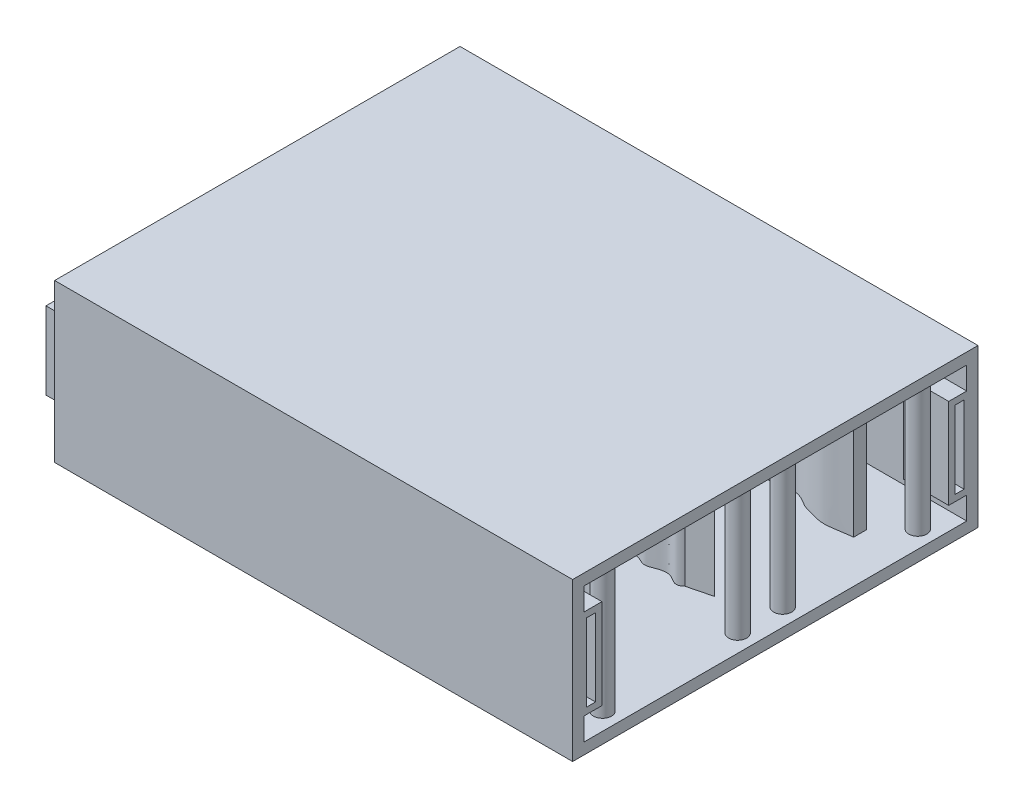
SolidWorks part; units mm, degrees
ref_plane "Спереди" through (0, 0, 0) normal (0, 0, 1) x (1, 0, 0)
ref_plane "Сверху" through (0, 0, 0) normal (0, 1, 0) x (1, 0, 0)
ref_plane "Справа" through (0, 0, 0) normal (1, 0, 0) x (0, 0, -1)
sketch "Эскиз1" plane through (0, 0, 0) normal (0, 1, 0) x (1, 0, 0)
  line L1 (-57.5, -45) -> (57.5, -45)
  line L2 (-57.5, -45) -> (-57.5, 45)
  line L3 (-57.5, 45) -> (57.5, 45)
  line L4 (57.5, -45) -> (57.5, 45)
  line L5 (-57.5, -45) -> (57.5, 45) construction
  line L6 (-57.5, 45) -> (57.5, -45) construction
  point P0 (0, 0)
extrude "Бобышка-Вытянуть1" add sketch "Эскиз1" along normal blind 35
sketch "Эскиз2" plane through (57.5, 0, 0) normal (1, 0, 0) x (0, 0, -1)
  line L0 (0, -1000) -> (0, 49000) construction
  line L1 (-1045, 17.5) -> (48955, 17.5) construction
  line L2 (-45, 35) -> (-45, 0) construction
  line L4 (-42.5, 2.5) -> (42.5, 2.5)
  line L5 (-42.5, 2.5) -> (-42.5, 32.5)
  line L6 (-42.5, 32.5) -> (42.5, 32.5)
  line L7 (42.5, 2.5) -> (42.5, 32.5)
  line L8 (-42.5, 2.5) -> (42.5, 32.5) construction
  line L9 (-42.5, 32.5) -> (42.5, 2.5) construction
  point P4 (0, 17.5)
  point P8 (-45, 17.5)
extrude "Вырез-Вытянуть1" cut sketch "Эскиз2" against normal through all
sketch "Эскиз3" plane through (57.5, 0, 0) normal (1, 0, 0) x (0, 0, -1)
  line L0 (38.5, 27.5) -> (42.5, 27.5)
  line L1 (-42.5, 32.5) -> (-42.5, 2.5) construction
  line L2 (42.5, 27.5) -> (42.5, 7.5)
  line L3 (-42.5, 7.5) -> (-42.5, 27.5)
  line L4 (-42.5, 27.5) -> (-38.5, 27.5)
  line L5 (-38.5, 27.5) -> (-38.5, 7.5)
  line L6 (-38.5, 7.5) -> (-42.5, 7.5)
  line L7 (42.5, 7.5) -> (38.5, 7.5)
  line L8 (38.5, 7.5) -> (38.5, 27.5)
  dimension "D1" = 2
extrude "Бобышка-Вытянуть2" add sketch "Эскиз3" against normal blind 10
pattern_linear "Линейный массив1" count 2 spacing 105 along (-1, 0, 0) of "Бобышка-Вытянуть2"
sketch "Эскиз4" plane through (-57.5, 0, 0) normal (-1, 0, 0) x (0, 0, 1)
  line L2 (-39.9142, 8.9142) -> (-39.9142, 26.0858)
  line L3 (-39.9142, 26.0858) -> (-41.9142, 26.0858)
  line L4 (-41.9142, 26.0858) -> (-41.9142, 8.9142)
  line L5 (-41.9142, 8.9142) -> (-39.9142, 8.9142)
  line L6 (39.9142, 8.9142) -> (39.9142, 26.0858)
  line L7 (39.9142, 26.0858) -> (41.9184, 26.0858)
  line L8 (41.9184, 26.0858) -> (41.9184, 8.9142)
  line L9 (41.9184, 8.9142) -> (39.9142, 8.9142)
extrude "Бобышка-Вытянуть3" add sketch "Эскиз4" along normal blind 5
sketch "Эскиз5" plane through (57.5, 0, 0) normal (1, 0, 0) x (0, 0, -1)
  line L1 (39.9142, 26.0858) -> (41.9142, 26.0858)
  line L2 (-39.9142, 8.9142) -> (-39.9142, 26.0858)
  line L3 (-41.8615, 26.0858) -> (-41.9142, 26.0858)
  line L4 (-41.9142, 26.0858) -> (-39.9142, 26.0858)
  line L5 (-41.9142, 26.0858) -> (-41.9142, 8.9142)
  line L6 (-41.9142, 8.9142) -> (-39.9142, 8.9142)
  line L7 (41.9142, 26.0858) -> (41.9142, 8.9142)
  line L8 (41.9142, 8.9142) -> (39.9142, 8.9142)
  line L9 (39.9142, 8.9142) -> (39.9142, 26.0858)
extrude "Вырез-Вытянуть2" cut sketch "Эскиз5" against normal blind 5 contours L5 L6 L2 L4 L3 | L9 L8 L7 L1
sketch "Эскиз6" plane through (0, 2.5, 0) normal (0, 1, 0) x (1, 0, 0)
  line L2 (-46.0433, 8.2412) -> (-46.0433, 6.421)
  line L3 (-46.0433, -8.2412) -> (-46.0433, -6.421)
  line L4 (-8.1582, 11.8084) -> (-8.1582, 10.8243)
  line L5 (-8.1582, -11.8084) -> (-8.1582, -10.8243)
  line L6 (3.0352, 28.6599) -> (3.0352, 26.8012)
  line L7 (3.0352, -28.6599) -> (3.0352, -26.8012)
  line L8 (48.0545, 29.6439) -> (48.0545, 26.8012)
  line L9 (48.0545, -29.6439) -> (48.0545, -26.8012)
  line L12 (38.7427, 1.3315) -> (43.9954, 0)
  line L13 (38.7427, -1.3315) -> (43.9954, 0)
  line L14 (5.3057, 0.9403) -> (1.7103, 0)
  line L15 (5.3057, -0.9403) -> (1.7103, 0)
  spline S0 degree 3 poles (-46.0433, 8.2412) (-43.7421, 7.0712) (-39.4784, 8.2572) (-34.0078, 11.3843) (-27.9935, 11.7331) (-23.0026, 8.3658) (-15.5011, 8.856) (-11.9371, 13.5591) (-8.1582, 11.8084) knots 0 0 0 0 0.182781 0.315256 0.483432 0.602003 0.761083 1 1 1 1
  spline S1 degree 3 poles (-46.0433, -8.2412) (-43.7421, -7.0712) (-39.4784, -8.2572) (-34.0078, -11.3843) (-27.9935, -11.7331) (-23.0026, -8.3658) (-15.5011, -8.856) (-11.9371, -13.5591) (-8.1582, -11.8084) knots 0 0 0 0 0.182781 0.315256 0.483432 0.602003 0.761083 1 1 1 1
  spline S2 degree 3 poles (3.0352, 28.6599) (5.7308, 30.3357) (11.3056, 31.2251) (17.9095, 26.7103) (24.746, 28.1237) (31.2421, 31.5672) (38.8642, 27.6886) (45.0279, 26.8022) (48.0545, 29.6439) knots 0 0 0 0 0.205733 0.319851 0.488896 0.620938 0.765565 1 1 1 1
  spline S3 degree 3 poles (3.0352, -28.6599) (5.7308, -30.3357) (11.3056, -31.2251) (17.9095, -26.7103) (24.746, -28.1237) (31.2421, -31.5672) (38.8642, -27.6886) (45.0279, -26.8022) (48.0545, -29.6439) knots 0 0 0 0 0.205733 0.319851 0.488896 0.620938 0.765565 1 1 1 1
  spline S4 degree 3 poles (-46.0433, 6.421) (-45.5676, 6.783) (-44.4183, 6.6635) (-42.5968, 6.252) (-40.6755, 6.8619) (-38.947, 7.5486) (-37.3717, 8.2728) (-35.9222, 9.1358) (-34.368, 9.7951) (-32.5524, 10.2365) (-30.8751, 10.4841) (-29.2057, 10.0746) (-27.7221, 9.7288) (-26.0326, 9.1727) (-24.419, 8.156) (-22.5797, 7.4979) (-20.5124, 7.6511) (-18.4237, 7.7038) (-16.431, 8.8517) (-14.5367, 9.6878) (-12.9332, 10.9205) (-10.7592, 11.5161) (-9.0869, 11.3699) (-8.1582, 10.8243) knots 0 0 0 0 0.041686 0.082662 0.139028 0.187024 0.22312 0.268386 0.313304 0.348627 0.408584 0.437027 0.476454 0.522986 0.568955 0.61917 0.665389 0.723193 0.772338 0.834418 0.878554 0.921772 1 1 1 1
  spline S5 degree 3 poles (-46.0433, -6.421) (-45.5676, -6.783) (-44.4183, -6.6635) (-42.5968, -6.252) (-40.6755, -6.8619) (-38.947, -7.5486) (-37.3717, -8.2728) (-35.9222, -9.1358) (-34.368, -9.7951) (-32.5524, -10.2365) (-30.8751, -10.4841) (-29.2057, -10.0746) (-27.7221, -9.7288) (-26.0326, -9.1727) (-24.419, -8.156) (-22.5797, -7.4979) (-20.5124, -7.6511) (-18.4237, -7.7038) (-16.431, -8.8517) (-14.5367, -9.6878) (-12.9332, -10.9205) (-10.7592, -11.5161) (-9.0869, -11.3699) (-8.1582, -10.8243) knots 0 0 0 0 0.041686 0.082662 0.139028 0.187024 0.22312 0.268386 0.313304 0.348627 0.408584 0.437027 0.476454 0.522986 0.568955 0.61917 0.665389 0.723193 0.772338 0.834418 0.878554 0.921772 1 1 1 1
  spline S6 degree 3 poles (3.0352, 26.8012) (4.5327, 27.5866) (6.4341, 29.0654) (9.093, 28.9982) (10.2266, 28.4562) (11.4665, 28.2431) (12.7306, 27.7946) (14.2593, 27.2906) (16.0122, 26.465) (18.2233, 26.1483) (20.6462, 25.8486) (22.9995, 26.3015) (25.2825, 27.0627) (27.1697, 28.3) (29.2098, 28.8951) (31.1988, 29.0558) (33.2315, 29.152) (35.1044, 28.3801) (36.7544, 27.2044) (38.7976, 26.8575) (41.0011, 26.0539) (44.2057, 26.1287) (46.5076, 26.719) (48.0545, 26.8012) knots 0 0 0 0 0.110987 0.140256 0.164303 0.1902 0.220041 0.2497 0.292932 0.342679 0.391189 0.447844 0.493596 0.543981 0.590585 0.627098 0.671558 0.718423 0.753047 0.799494 0.848039 0.901888 1 1 1 1
  spline S7 degree 3 poles (3.0352, -26.8012) (4.5327, -27.5866) (6.4341, -29.0654) (9.093, -28.9982) (10.2266, -28.4562) (11.4665, -28.2431) (12.7306, -27.7946) (14.2593, -27.2906) (16.0122, -26.465) (18.2233, -26.1483) (20.6462, -25.8486) (22.9995, -26.3015) (25.2825, -27.0627) (27.1697, -28.3) (29.2098, -28.8951) (31.1988, -29.0558) (33.2315, -29.152) (35.1044, -28.3801) (36.7544, -27.2044) (38.7976, -26.8575) (41.0011, -26.0539) (44.2057, -26.1287) (46.5076, -26.719) (48.0545, -26.8012) knots 0 0 0 0 0.110987 0.140256 0.164303 0.1902 0.220041 0.2497 0.292932 0.342679 0.391189 0.447844 0.493596 0.543981 0.590585 0.627098 0.671558 0.718423 0.753047 0.799494 0.848039 0.901888 1 1 1 1
  spline S8 degree 3 poles (5.3057, 0.9403) (5.9635, 1.5316) (7.3945, 1.952) (9.4015, 1.3006) (11.1649, 1.2949) (12.979, 2.1733) (14.8129, 2.0105) (16.5267, 1.2271) (18.361, 0.8984) (20.4838, 0.6689) (22.1421, 1.8032) (24.0559, 2.1383) (25.7651, 1.1451) (27.9202, 0.5843) (30.1177, 2.2316) (32.5338, 0.7565) (35.7943, 0.5479) (37.2802, 2.6987) (38.7427, 1.3315) knots 0 0 0 0 0.07628 0.116788 0.181741 0.222476 0.288888 0.331771 0.385342 0.451021 0.507182 0.554429 0.609586 0.674865 0.733613 0.820119 0.891781 1 1 1 1
  spline S9 degree 3 poles (5.3057, -0.9403) (5.9635, -1.5316) (7.3945, -1.952) (9.4015, -1.3006) (11.1649, -1.2949) (12.979, -2.1733) (14.8129, -2.0105) (16.5267, -1.2271) (18.361, -0.8984) (20.4838, -0.6689) (22.1421, -1.8032) (24.0559, -2.1383) (25.7651, -1.1451) (27.9202, -0.5843) (30.1177, -2.2316) (32.5338, -0.7565) (35.7943, -0.5479) (37.2802, -2.6987) (38.7427, -1.3315) knots 0 0 0 0 0.07628 0.116788 0.181741 0.222476 0.288888 0.331771 0.385342 0.451021 0.507182 0.554429 0.609586 0.674865 0.733613 0.820119 0.891781 1 1 1 1
extrude "Бобышка-Вытянуть4" add sketch "Эскиз6" along normal blind 32
sketch "Эскиз7" plane through (0, 2.5, 0) normal (0, 1, 0) x (1, 0, 0)
  circle A0 centre (-54.1615, 35.5481) radius 2
  circle A3 centre (-54.1615, 5.5481) radius 2
  circle A4 centre (-54.1615, -4.4519) radius 2
  circle A6 centre (-39.1615, 35.5481) radius 2
  circle A8 centre (-9.1615, 35.5481) radius 2
  circle A9 centre (5.8385, 35.5481) radius 2
  circle A11 centre (35.8385, 35.5481) radius 2
  circle A13 centre (-54.1615, -34.4519) radius 2
  circle A14 centre (-39.1615, -34.4519) radius 2
  circle A16 centre (-9.1615, -34.4519) radius 2
  circle A17 centre (5.8385, -34.4519) radius 2
  circle A19 centre (35.8385, -34.4519) radius 2
  circle A20 centre (53.5897, 35.5481) radius 2
  circle A23 centre (53.5897, 5.5481) radius 2
  circle A24 centre (53.5897, -4.4519) radius 2
  circle A27 centre (53.5897, -34.4519) radius 2
  circle A28 centre (-24.1615, 35.5481) radius 2 [skipped]
  circle A29 centre (20.8385, 35.5481) radius 2 [skipped]
  circle A30 centre (-24.1615, -34.4519) radius 2 [skipped]
  circle A31 centre (20.8385, -34.4519) radius 2 [skipped]
  circle A32 centre (-54.1615, -14.4519) radius 2 [skipped]
  circle A33 centre (-54.1615, 15.5481) radius 2 [skipped]
  circle A34 centre (53.5897, 15.5481) radius 2 [skipped]
  circle A35 centre (53.5897, -14.4519) radius 2 [skipped]
  circle A36 centre (-22.7956, 20.5416) radius 3
  circle A37 centre (-22.7956, -20.4186) radius 3
  circle A38 centre (-54.1615, -24.4519) radius 2 [skipped]
  circle A39 centre (-54.1615, 25.5481) radius 2 [skipped]
  circle A40 centre (53.5897, 25.5481) radius 2 [skipped]
  circle A41 centre (53.5897, -24.4519) radius 2 [skipped]
  dimension "D1" = 8
  dimension "D4" = 8
  dimension "D2" = 7
  dimension "D3" = 7
extrude "Бобышка-Вытянуть5" add sketch "Эскиз7" along normal blind 32
